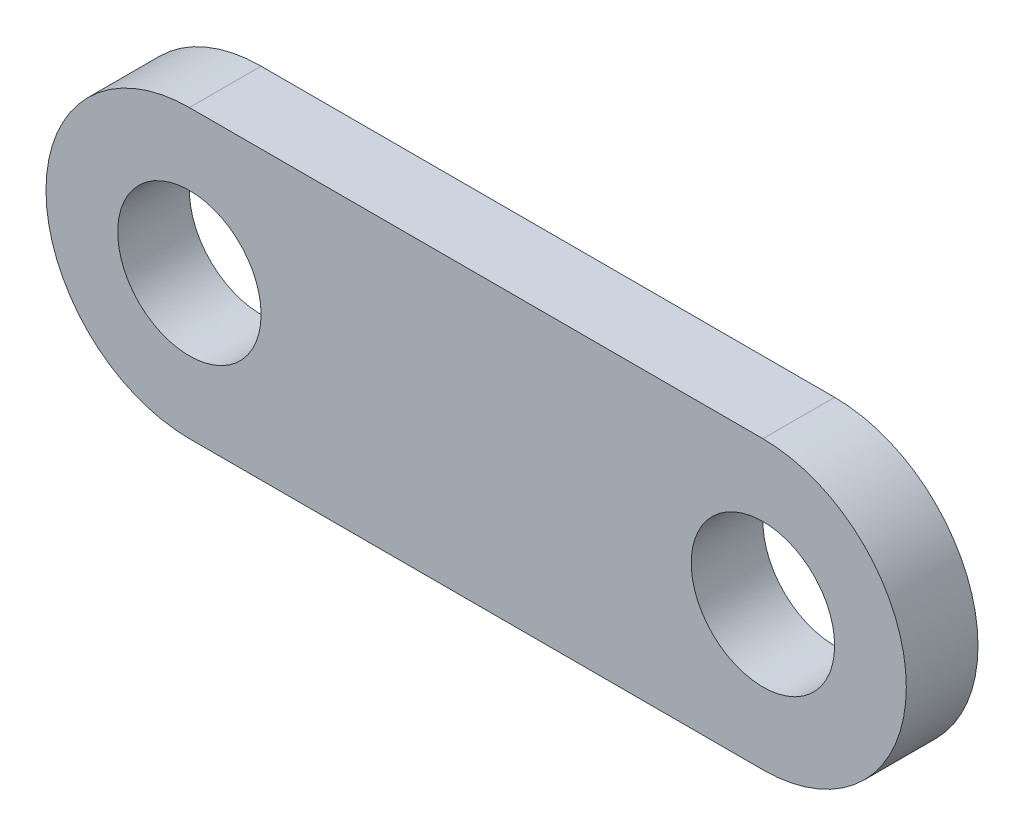
SolidWorks part; units mm, degrees
ref_plane "Ön Düzlem" through (0, 0, 0) normal (0, 0, 1) x (1, 0, 0)
ref_plane "Üst Düzlem" through (0, 0, 0) normal (0, 1, 0) x (1, 0, 0)
ref_plane "Sağ Düzlem" through (0, 0, 0) normal (1, 0, 0) x (0, 0, -1)
sketch "Çizim1" plane through (0, 0, 0) normal (0, 0, 1) x (1, 0, 0)
  line L0 (-38.6982, 2.8866) -> (1.3018, 2.8866) construction
  line L1 (-38.6982, 12.8866) -> (1.3018, 12.8866)
  line L2 (-38.6982, -7.1134) -> (1.3018, -7.1134)
  arc A0 (-38.6982, 12.8866) -> (-38.6982, -7.1134) centre (-38.6982, 2.8866) ccw
  arc A1 (1.3018, -7.1134) -> (1.3018, 12.8866) centre (1.3018, 2.8866) ccw
  circle A2 centre (-38.6982, 2.8866) radius 5
  circle A3 centre (1.3018, 2.8866) radius 5
  point P2 (-18.6982, 2.8866)
  dimension "D1" = 40
  dimension "D2" = 20
extrude "Yükseklik-Ekstrüzyon1" add sketch "Çizim1" along normal blind 5
